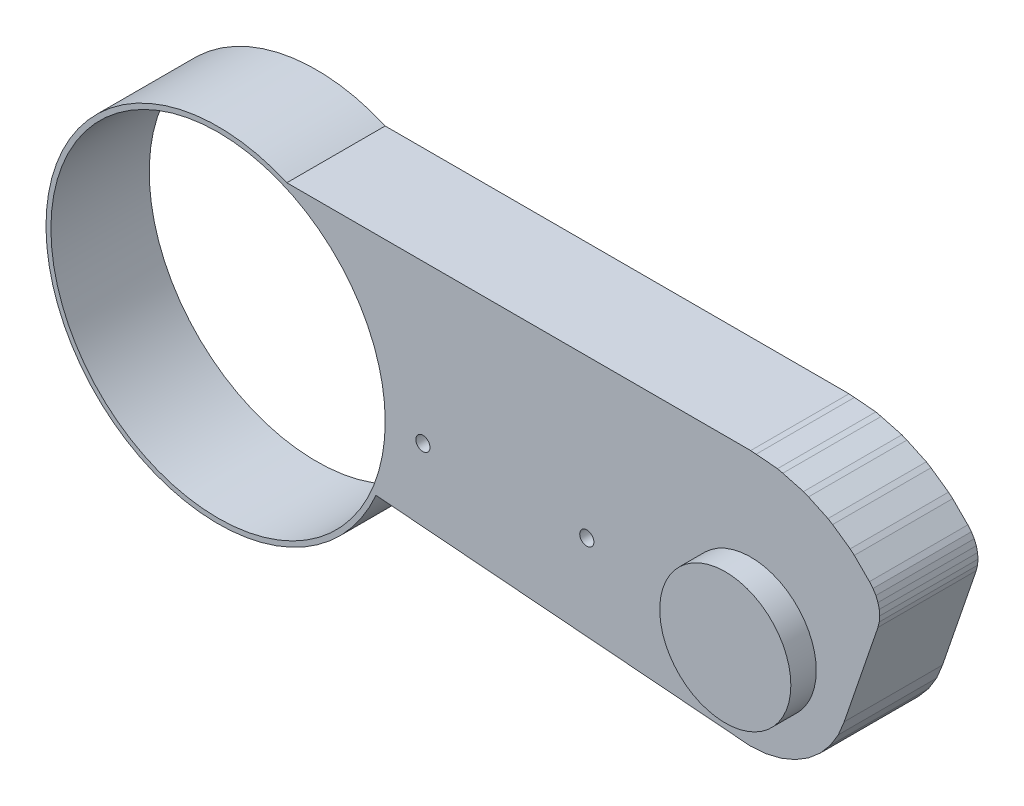
SolidWorks part; units mm, degrees
ref_plane "Front Plane" through (0, 0, 0) normal (0, 0, 1) x (1, 0, 0)
ref_plane "Top Plane" through (0, 0, 0) normal (0, 1, 0) x (1, 0, 0)
ref_plane "Right Plane" through (0, 0, 0) normal (1, 0, 0) x (0, 0, -1)
sketch "Sketch1" plane through (0, 0, 0) normal (0, 0, 1) x (1, 0, 0)
  circle A0 centre (0, 0) radius 42
extrude "Boss-Extrude1" add sketch "Sketch1" along normal blind 24 from offset 3
sketch "Sketch2" plane through (0, 0, 0) normal (0, 0, 1) x (1, 0, 0)
  line L0 (-38.5, 0) -> (-38.3954, -1.3297)
  line L1 (-38.3954, -1.3297) -> (-38.084, -2.6266)
  line L2 (-38.084, -2.6266) -> (-37.5736, -3.8589)
  line L3 (-37.5736, -3.8589) -> (-36.8766, -4.9962)
  line L4 (-36.8766, -4.9962) -> (-36.0104, -6.0104)
  line L5 (-36.0104, -6.0104) -> (-34.9962, -6.8766)
  line L6 (-34.9962, -6.8766) -> (-33.8589, -7.5736)
  line L7 (-33.8589, -7.5736) -> (-32.6266, -8.084)
  line L8 (-32.6266, -8.084) -> (-31.3297, -8.3954)
  line L9 (-31.3297, -8.3954) -> (27.497, -15.803)
  line L10 (27.497, -15.803) -> (126.2456, -23.7045)
  line L11 (126.2456, -23.7045) -> (130, -24)
  line L12 (130, -24) -> (133.7544, -23.7045)
  line L13 (133.7544, -23.7045) -> (137.4164, -22.8254)
  line L14 (137.4164, -22.8254) -> (140.8958, -21.3842)
  line L15 (140.8958, -21.3842) -> (144.1068, -19.4164)
  line L16 (144.1068, -19.4164) -> (146.9706, -16.9706)
  line L17 (146.9706, -16.9706) -> (149.4164, -14.1068)
  line L18 (149.4164, -14.1068) -> (151.3842, -10.8958)
  line L19 (151.3842, -10.8958) -> (152.8254, -7.4164)
  line L20 (152.8254, -7.4164) -> (161.0653, 16.657)
  line L21 (161.0653, 16.657) -> (161.3767, 17.9539)
  line L22 (161.3767, 17.9539) -> (161.4813, 19.2836)
  line L23 (161.4813, 19.2836) -> (161.3767, 20.6133)
  line L24 (161.3767, 20.6133) -> (161.0653, 21.9103)
  line L25 (161.0653, 21.9103) -> (160.5549, 23.1425)
  line L26 (160.5549, 23.1425) -> (159.858, 24.2798)
  line L27 (159.858, 24.2798) -> (158.9917, 25.294)
  line L28 (158.9917, 25.294) -> (155.294, 28.9917)
  line L29 (155.294, 28.9917) -> (154.2798, 29.858)
  line L30 (154.2798, 29.858) -> (149.9962, 32.8574)
  line L31 (149.9962, 32.8574) -> (148.8589, 33.5543)
  line L32 (148.8589, 33.5543) -> (144.1195, 35.7643)
  line L33 (144.1195, 35.7643) -> (142.8872, 36.2748)
  line L34 (142.8872, 36.2748) -> (137.8361, 37.6282)
  line L35 (137.8361, 37.6282) -> (136.5391, 37.9396)
  line L36 (136.5391, 37.9396) -> (131.3297, 38.3954)
  line L37 (131.3297, 38.3954) -> (130, 38.5)
  line L38 (130, 38.5) -> (0, 38.5)
  line L39 (0, 38.5) -> (-1.3297, 38.3954)
  line L40 (-1.3297, 38.3954) -> (-6.5391, 37.9396)
  line L41 (-6.5391, 37.9396) -> (-7.8361, 37.6282)
  line L42 (-7.8361, 37.6282) -> (-12.8872, 36.2748)
  line L43 (-12.8872, 36.2748) -> (-14.1195, 35.7643)
  line L44 (-14.1195, 35.7643) -> (-18.8589, 33.5543)
  line L45 (-18.8589, 33.5543) -> (-19.9962, 32.8574)
  line L46 (-19.9962, 32.8574) -> (-24.2798, 29.858)
  line L47 (-24.2798, 29.858) -> (-25.294, 28.9917)
  line L48 (-25.294, 28.9917) -> (-28.9917, 25.294)
  line L49 (-28.9917, 25.294) -> (-29.858, 24.2798)
  line L50 (-29.858, 24.2798) -> (-32.8574, 19.9962)
  line L51 (-32.8574, 19.9962) -> (-33.5543, 18.8589)
  line L52 (-33.5543, 18.8589) -> (-35.7643, 14.1195)
  line L53 (-35.7643, 14.1195) -> (-36.2748, 12.8872)
  line L54 (-36.2748, 12.8872) -> (-37.6282, 7.8361)
  line L55 (-37.6282, 7.8361) -> (-37.9396, 6.5391)
  line L56 (-37.9396, 6.5391) -> (-38.3954, 1.3297)
  line L57 (-38.3954, 1.3297) -> (-38.5, 0)
extrude "Boss-Extrude2" add sketch "Sketch2" along normal blind 24 from offset 3
sketch "Sketch3" plane through (0, 0, 0) normal (0, 0, 1) x (1, 0, 0)
  line L0 (-37.3, 0) -> (-37.2101, -1.142)
  line L1 (-37.2101, -1.142) -> (-36.9427, -2.2558)
  line L2 (-36.9427, -2.2558) -> (-36.5043, -3.3141)
  line L3 (-36.5043, -3.3141) -> (-35.9058, -4.2908)
  line L4 (-35.9058, -4.2908) -> (-35.1619, -5.1619)
  line L5 (-35.1619, -5.1619) -> (-34.2908, -5.9058)
  line L6 (-34.2908, -5.9058) -> (-33.3141, -6.5043)
  line L7 (-33.3141, -6.5043) -> (-32.2558, -6.9427)
  line L8 (-32.2558, -6.9427) -> (-31.142, -7.2101)
  line L9 (-31.142, -7.2101) -> (27.6848, -14.6178)
  line L10 (27.6848, -14.6178) -> (126.4333, -22.5193)
  line L11 (126.4333, -22.5193) -> (130, -22.8)
  line L12 (130, -22.8) -> (133.5667, -22.5193)
  line L13 (133.5667, -22.5193) -> (137.0456, -21.6841)
  line L14 (137.0456, -21.6841) -> (140.351, -20.3149)
  line L15 (140.351, -20.3149) -> (143.4015, -18.4456)
  line L16 (143.4015, -18.4456) -> (146.122, -16.122)
  line L17 (146.122, -16.122) -> (148.4456, -13.4015)
  line L18 (148.4456, -13.4015) -> (150.3149, -10.351)
  line L19 (150.3149, -10.351) -> (151.6841, -7.0456)
  line L20 (151.6841, -7.0456) -> (159.924, 17.0278)
  line L21 (159.924, 17.0278) -> (160.1915, 18.1417)
  line L22 (160.1915, 18.1417) -> (160.2813, 19.2836)
  line L23 (160.2813, 19.2836) -> (160.1915, 20.4256)
  line L24 (160.1915, 20.4256) -> (159.924, 21.5395)
  line L25 (159.924, 21.5395) -> (159.4857, 22.5978)
  line L26 (159.4857, 22.5978) -> (158.8872, 23.5745)
  line L27 (158.8872, 23.5745) -> (158.1432, 24.4455)
  line L28 (158.1432, 24.4455) -> (154.4455, 28.1432)
  line L29 (154.4455, 28.1432) -> (153.5745, 28.8872)
  line L30 (153.5745, 28.8872) -> (149.2908, 31.8866)
  line L31 (149.2908, 31.8866) -> (148.3141, 32.4851)
  line L32 (148.3141, 32.4851) -> (143.5747, 34.6951)
  line L33 (143.5747, 34.6951) -> (142.5164, 35.1335)
  line L34 (142.5164, 35.1335) -> (137.4653, 36.4869)
  line L35 (137.4653, 36.4869) -> (136.3514, 36.7544)
  line L36 (136.3514, 36.7544) -> (131.142, 37.2101)
  line L37 (131.142, 37.2101) -> (130, 37.3)
  line L38 (130, 37.3) -> (0, 37.3)
  line L39 (0, 37.3) -> (-1.142, 37.2101)
  line L40 (-1.142, 37.2101) -> (-6.3514, 36.7544)
  line L41 (-6.3514, 36.7544) -> (-7.4653, 36.4869)
  line L42 (-7.4653, 36.4869) -> (-12.5164, 35.1335)
  line L43 (-12.5164, 35.1335) -> (-13.5747, 34.6951)
  line L44 (-13.5747, 34.6951) -> (-18.3141, 32.4851)
  line L45 (-18.3141, 32.4851) -> (-19.2908, 31.8866)
  line L46 (-19.2908, 31.8866) -> (-23.5745, 28.8872)
  line L47 (-23.5745, 28.8872) -> (-24.4455, 28.1432)
  line L48 (-24.4455, 28.1432) -> (-28.1432, 24.4455)
  line L49 (-28.1432, 24.4455) -> (-28.8872, 23.5745)
  line L50 (-28.8872, 23.5745) -> (-31.8866, 19.2908)
  line L51 (-31.8866, 19.2908) -> (-32.4851, 18.3141)
  line L52 (-32.4851, 18.3141) -> (-34.6951, 13.5747)
  line L53 (-34.6951, 13.5747) -> (-35.1335, 12.5164)
  line L54 (-35.1335, 12.5164) -> (-36.4869, 7.4653)
  line L55 (-36.4869, 7.4653) -> (-36.7544, 6.3514)
  line L56 (-36.7544, 6.3514) -> (-37.2101, 1.142)
  line L57 (-37.2101, 1.142) -> (-37.3, 0)
extrude "Cut-Extrude1" cut sketch "Sketch3" along normal blind 22.8 from offset 3
sketch "Sketch4" plane through (0, 0, 0) normal (0, 0, 1) x (1, 0, 0)
  circle A0 centre (0, 0) radius 40.8
extrude "Cut-Extrude2" cut sketch "Sketch4" against normal through all and the other way through all
sketch "Sketch5" plane through (0, 0, 0) normal (0, 0, 1) x (1, 0, 0)
  circle A0 centre (130, 0) radius 16
extrude "Boss-Extrude3" add sketch "Sketch5" along normal blind 6.2 from offset 21
sketch "Sketch6" plane through (0, 0, 0) normal (0, 0, 1) x (1, 0, 0)
  circle A0 centre (130, 0) radius 14.8
extrude "Cut-Extrude3" cut sketch "Sketch6" along normal blind 6.2 from offset 19.8
sketch "Sketch7" plane through (0, 0, 0) normal (0, 0, 1) x (1, 0, 0)
  circle A0 centre (50, 0) radius 3.5
  circle A1 centre (90, 0) radius 3.5
extrude "Boss-Extrude4" add sketch "Sketch7" along normal blind 10.8 from offset 9
sketch "Sketch8" plane through (0, 0, 0) normal (0, 0, 1) x (1, 0, 0)
  circle A0 centre (50, 0) radius 1.725
  circle A1 centre (90, 0) radius 1.725
extrude "Cut-Extrude4" cut sketch "Sketch8" against normal through all and the other way through all
